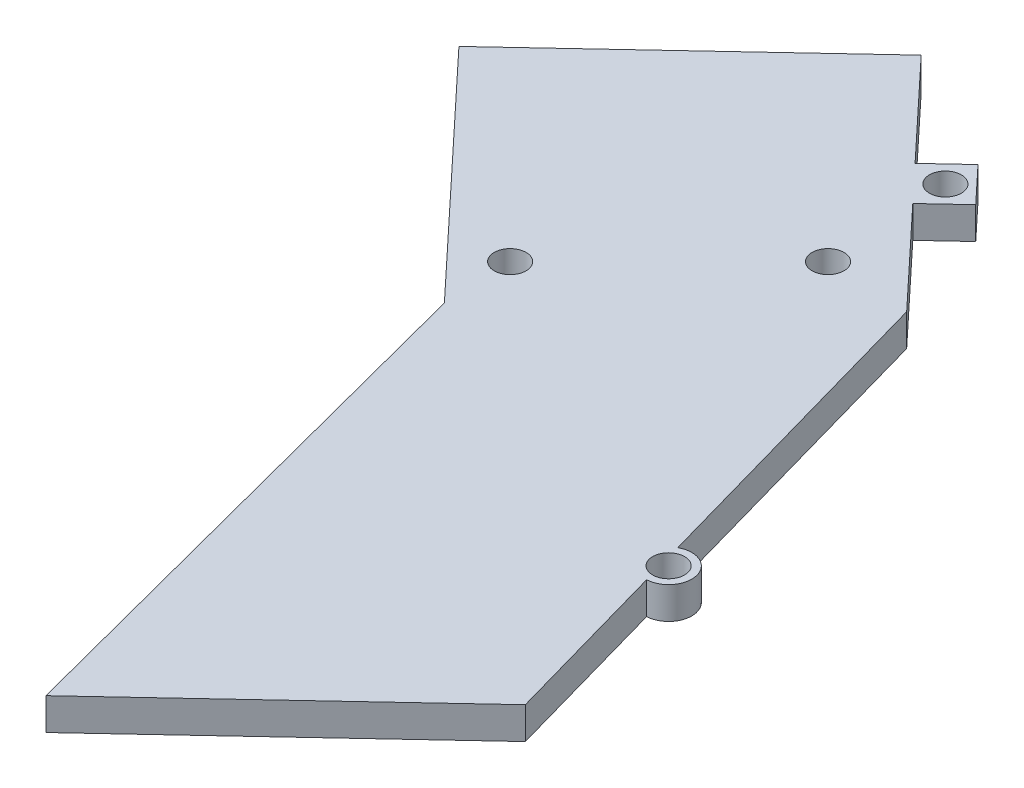
SolidWorks part; units mm, degrees
ref_plane "Front Plane" through (0, 0, 0) normal (0, 0, 1) x (1, 0, 0)
ref_plane "Top Plane" through (0, 0, 0) normal (0, 1, 0) x (1, 0, 0)
ref_plane "Right Plane" through (0, 0, 0) normal (1, 0, 0) x (0, 0, -1)
ref_plane "Plane1" through (0, 0, 0) normal (0, 1, 0) x (1, 0, 0)
sketch "Sketch1" plane through (0, 0, 0) normal (0, 1, 0) x (1, 0, 0)
  line L1 (15.2438, 108.2324) -> (-2.7837, 127.4797) construction
  line L2 (-27.496, 153.8638) -> (-74.9669, 109.4011) construction
  line L4 (15.2438, 108.2324) -> (33.1183, 44.8363) construction
  line L5 (45.0177, 2.6318) -> (-4.2088, -43.4753) construction
  line L6 (-4.2088, -43.4753) -> (-32.2271, 63.7697) construction
  line L7 (45.0177, 2.6318) -> (35.5507, 36.2092)
  line L8 (15.2438, 108.2324) -> (-2.7837, 127.4797)
  line L9 (-27.496, 153.8638) -> (-74.9669, 109.4011)
  line L10 (-74.9669, 109.4011) -> (-32.2271, 63.7697)
  line L11 (-32.2271, 63.7697) -> (-4.2088, -43.4753)
  line L13 (45.0177, 2.6318) -> (-4.2088, -43.4753)
  line L15 (35.5507, 36.2092) -> (45.0177, 2.6318) construction
  line L16 (33.1183, 44.8363) -> (15.2438, 108.2324)
  line L17 (-32.8086, 77.4293) -> (-1.2, 109.0418) construction
  line L19 (-4.2088, -43.4753) -> (-17.3046, 6.6513) construction
  line L20 (0.3363, 130.3833) -> (0.3273, 130.3935) construction
  line L21 (-17.3046, 6.6513) -> (-13.163, 7.6893) construction
  line L22 (-6.1168, 137.7559) -> (-9.4684, 134.6166) construction
  line L23 (-3.0026, 140.4816) -> (-2.8851, 140.5844) construction
  line L24 (-17.3046, 6.6513) -> (-13.163, 7.6893) construction
  line L26 (3.679, 133.5328) -> (-2.7837, 127.4797)
  line L27 (3.679, 133.5328) -> (-3.0057, 140.6698)
  line L29 (-3.0057, 140.6698) -> (-9.4684, 134.6166)
  line L32 (-9.4684, 134.6166) -> (-27.496, 153.8638) construction
  line L33 (-9.4684, 134.6166) -> (-27.496, 153.8638)
  line L34 (-3.0026, 140.4816) -> (-3.0057, 140.6698) construction
  line L36 (0.3273, 130.3935) -> (0.3363, 130.3833) construction
  line L56 (-30.9936, 74.8242) -> (-32.8086, 77.4293) construction
  arc A1 (35.5507, 36.2092) -> (33.1183, 44.8363) centre (35.3343, 40.8046) ccw
  circle A4 centre (-2.8946, 134.0748) radius 3.175
  circle A5 centre (35.3343, 40.8046) radius 3.175
  circle A7 centre (-32.8086, 77.4293) radius 3.175
  circle A8 centre (-1.2, 109.0418) radius 3.175
  dimension "D1" = 6.35
  dimension "D2" = 6.35
  dimension "D8" = 6.35
  dimension "D9" = 44.704
  dimension "D12" = 4.2697
extrude "Boss-Extrude1" add sketch "Sketch1" along normal blind 6.35
